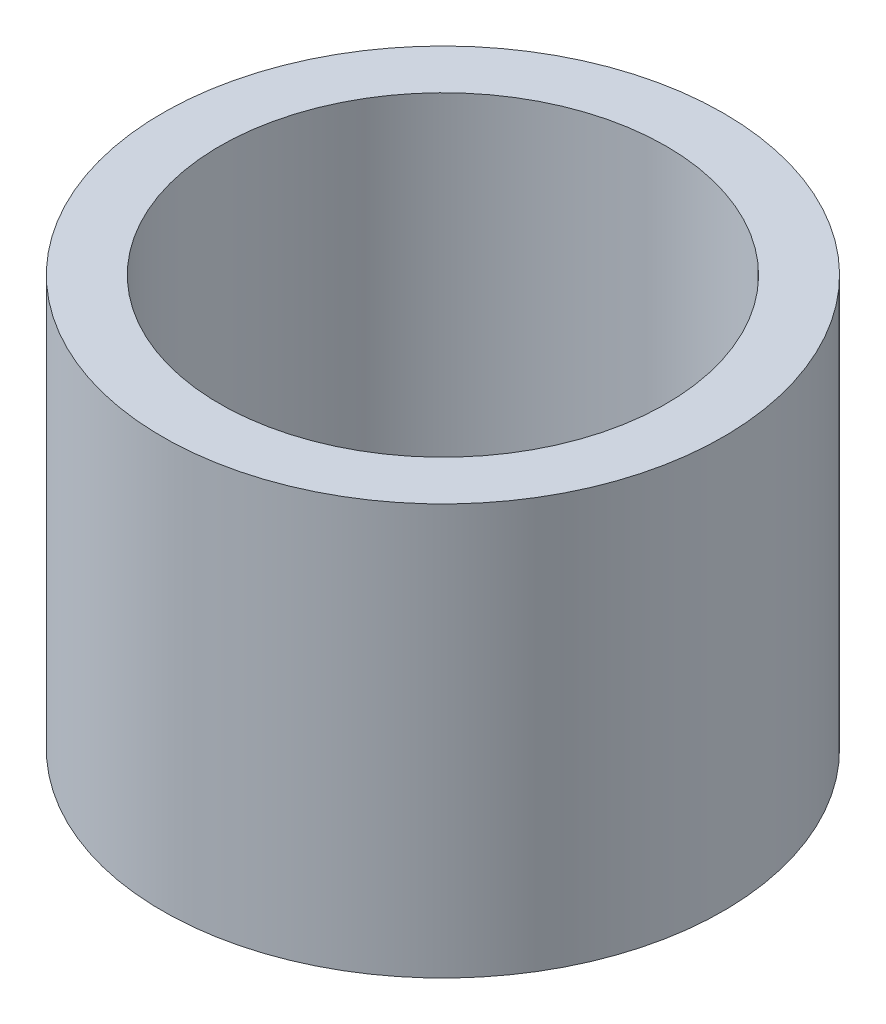
SolidWorks part; units mm, degrees
ref_plane "Alzado" through (0, 0, 0) normal (0, 0, 1) x (1, 0, 0)
ref_plane "Planta" through (0, 0, 0) normal (0, 1, 0) x (1, 0, 0)
ref_plane "Vista lateral" through (0, 0, 0) normal (1, 0, 0) x (0, 0, -1)
sketch "Croquis1" plane through (0, 0, 0) normal (1, 0, 0) x (0, 0, -1)
  line L0 (-39, 25.8696) -> (-39, -45.8696)
  line L1 (-39, -45.8696) -> (-49, -45.8696)
  line L2 (-49, -45.8696) -> (-49, 25.8696)
  line L3 (-49, 25.8696) -> (-39, 25.8696)
  line L4 (0, 0) -> (0, 25.8696) construction
  dimension "D1" = 39
  dimension "D2" = 10
revolve "Revolución1" add sketch "Croquis1" angle 360 about L4
